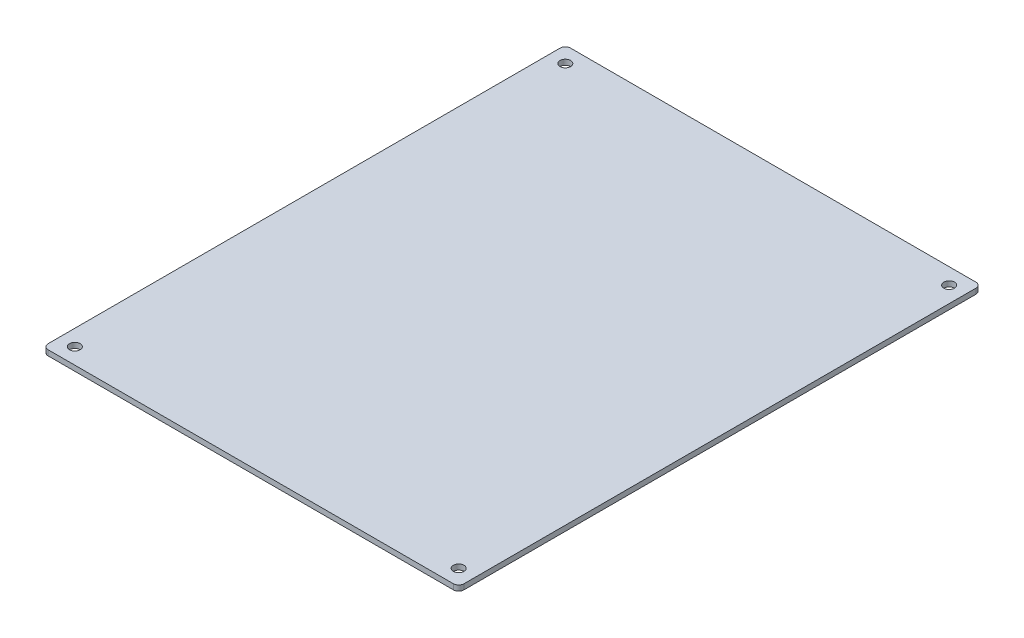
SolidWorks part; units mm, degrees
ref_plane "Front Plane" through (0, 0, 0) normal (0, 0, 1) x (1, 0, 0)
ref_plane "Top Plane" through (0, 0, 0) normal (0, 1, 0) x (1, 0, 0)
ref_plane "Right Plane" through (0, 0, 0) normal (1, 0, 0) x (0, 0, -1)
sketch "Sketch1" plane through (0, 0, 0) normal (0, 1, 0) x (1, 0, 0)
  line L1 (0, 0) -> (123.825, 0)
  line L2 (0, 0) -> (0, 155.575)
  line L3 (0, 155.575) -> (123.825, 155.575)
  line L4 (123.825, 0) -> (123.825, 155.575)
  circle A0 centre (4.7625, 150.8125) radius 1.5875
  circle A1 centre (119.0625, 150.8125) radius 1.5875
  circle A2 centre (119.0625, 4.7625) radius 1.5875
  circle A3 centre (4.7625, 4.7625) radius 1.5875
  dimension "D3" = 3.175
  dimension "D1" = 155.575
  dimension "D2" = 123.825
  dimension "D4" = 4.7625
  dimension "D5" = 4.7625
  dimension "D6" = 4.7625
  dimension "D7" = 4.7625
extrude "Boss-Extrude1" add sketch "Sketch1" along normal blind 1.5875
fillet "Fillet1" radius 1.5875 4 edges at (0, 0.7937, 0) (123.825, 0.7937, 0) (123.825, 0.7937, -155.575) (0, 0.7937, -155.575)
